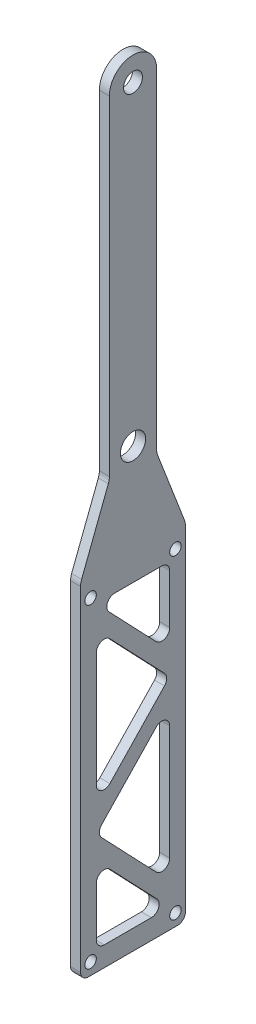
SolidWorks part; units mm, degrees
material "6061 Alloy"
ref_plane "Front Plane" through (0, 0, 0) normal (0, 0, 1) x (1, 0, 0)
ref_plane "Top Plane" through (0, 0, 0) normal (0, 1, 0) x (1, 0, 0)
ref_plane "Right Plane" through (0, 0, 0) normal (1, 0, 0) x (0, 0, -1)
sketch "Sketch1" plane through (0, 0, 0) normal (1, 0, 0) x (0, 0, -1)
  line L0 (-13.4747, 0) -> (13.4747, 0) construction
  line L1 (0, 0) -> (0, 35) construction
  line L2 (-13.4747, 0) -> (0, 35) construction
  line L3 (0, 35) -> (13.4747, 0) construction
  line L4 (13.4747, 0) -> (-13.4747, 0) construction
  line L5 (20.7574, -5) -> (-20.7574, -5)
  line L6 (-20.7574, -5) -> (0, 48.9165)
  line L7 (0, 48.9165) -> (20.7574, -5)
  line L8 (0, 35) -> (0, 135) construction
  line L9 (0, 35) -> (0, 135) construction
  line L12 (-7.5, 35) -> (-7.5, 135)
  line L13 (7.5, 35) -> (7.5, 135)
  line L14 (-7.5, 35) -> (-7.5, 29.4356)
  line L15 (7.5, 35) -> (7.5, 29.4356)
  line L16 (-13.4747, 0) -> (13.4747, 0) construction
  line L17 (-13.4747, 0) -> (-13.4747, -100) construction
  line L18 (13.4747, 0) -> (13.4747, -100) construction
  line L19 (-13.4747, -100) -> (13.4747, -100) construction
  line L20 (-20.7574, -5) -> (20.7574, -5)
  line L21 (-20.7574, -5) -> (-20.7574, -103.81)
  line L22 (20.7574, -5) -> (20.7574, -103.81)
  line L23 (-20.7574, -103.81) -> (20.7574, -103.81)
  circle A0 centre (-13.4747, 0) radius 1.8288
  circle A1 centre (0, 35) radius 4
  circle A2 centre (13.4747, 0) radius 1.8288
  circle A3 centre (0, 135) radius 3
  arc A6 (-7.5, 35) -> (7.5, 35) centre (0, 35) ccw
  arc A7 (7.5, 135) -> (-7.5, 135) centre (0, 135) ccw
  circle A8 centre (-13.4747, -100) radius 1.8288
  circle A9 centre (13.4747, -100) radius 1.8288
  point P4 (0, 0)
  point P14 (0, 85)
  dimension "D3" = 3.6576
  dimension "D4" = 8
  dimension "D7" = 6
  dimension "D1" = 26.9494
  dimension "D5" = 100
  dimension "D6" = 15
  dimension "D8" = 100
  dimension "D9" = 3.81
  dimension "D10" = 35
  dimension "D2" = 5
extrude "Boss-Extrude1" add sketch "Sketch1" along normal blind 3.175 contours A6 L6 L5 L7 A2 A0 | L6 A6 L7 A1 | L13 A7 L12 A6 L6 A1 L7 A3 | A1 L7 L6 | A6 L7 L15 | A6 L14 L6 | A8 | A9 | L20 L21 L23 L22
sketch "Sketch2" plane through (3.175, 0, 0) normal (1, 0, 0) x (0, 0, -1)
  line L0 (-11.645, -2.5) -> (11.645, -2.5) construction
  line L1 (-11.645, -97.5) -> (11.645, -97.5) construction
  line L2 (11.645, -97.5) -> (11.645, -2.5) construction
  line L3 (-11.645, -97.5) -> (-11.645, -2.5) construction
  line L6 (11.645, -37.7891) -> (-11.645, -62.2109) construction
  line L7 (11.645, -2.5) -> (-11.645, -2.5)
  line L8 (-11.645, -2.5) -> (11.645, -26.9218)
  line L9 (11.645, -26.9218) -> (11.645, -2.5)
  line L10 (-11.645, -9.7449) -> (11.645, -34.1667)
  line L11 (11.645, -34.1667) -> (-11.645, -58.5884)
  line L12 (-11.645, -58.5884) -> (-11.645, -34.1667)
  line L13 (-11.645, -34.1667) -> (-11.645, -9.7449)
  line L14 (-11.645, -73.0782) -> (-11.645, -97.5)
  line L15 (-11.645, -97.5) -> (11.645, -97.5)
  line L16 (11.645, -97.5) -> (-11.645, -73.0782)
  line L17 (11.645, -41.4116) -> (11.645, -65.8333)
  line L18 (11.645, -65.8333) -> (11.645, -90.2551)
  line L19 (11.645, -90.2551) -> (-11.645, -65.8333)
  line L20 (-11.645, -65.8333) -> (11.645, -41.4116)
  line L21 (16.645, -1056.0877) -> (16.645, 48943.9123) construction
  line L22 (-16.645, -1060.2922) -> (-16.645, 48939.7078) construction
  line L23 (16.645, 29.4356) -> (-16.645, 29.4356) construction
  line L24 (-20.7574, -103.81) -> (-16.645, -103.81)
  line L25 (-20.7574, -103.81) -> (-20.7574, 29.4356)
  line L26 (-16.645, -103.81) -> (-16.645, 29.4356)
  line L27 (-20.7574, 29.4356) -> (-16.645, 29.4356)
  line L28 (-20.7574, -103.81) -> (20.7574, -103.81) construction
  line L29 (20.7574, -103.81) -> (16.645, -103.81)
  line L30 (20.7574, -103.81) -> (20.7574, 29.4356)
  line L31 (16.645, -103.81) -> (16.645, 29.4356)
  line L32 (20.7574, 29.4356) -> (16.645, 29.4356)
  circle A0 centre (13.4747, 0) radius 1.8288 construction
  circle A1 centre (13.4747, -100) radius 1.8288 construction
  point P6 (11.645, -50)
  point P10 (0, 29.4356)
  point P21 (0, -50)
  dimension "D1" = 33.29
  dimension "D2" = 5
  dimension "D3" = 2.5
  dimension "D4" = 2.5
  dimension "D5" = 5
  dimension "D6" = 2.5
  dimension "D8" = 5
  dimension "D7" = 2
extrude "Cut-Extrude1" cut sketch "Sketch2" against normal up to next
fillet "Fillet3" radius 2.5 14 edges at (1.5875, -58.5884, 11.645) (1.5875, -34.1667, -11.645) (1.5875, -97.5, -11.645) (1.5875, -73.0782, 11.645) (1.5875, -97.5, 11.645) (1.5875, -26.9218, -11.645) (1.5875, -2.5, -11.645) (1.5875, -9.7449, 11.645) (1.5875, -2.5, 11.645) (1.5875, -90.2551, -11.645) (1.5875, -41.4116, -11.645) (1.5875, -65.8333, 11.645) (1.5875, -103.81, 16.645) (1.5875, -103.81, -16.645)
fillet "Fillet4" radius 5 4 edges at (1.5875, 29.4356, -7.5) (1.5875, 29.4356, 7.5) (1.5875, 5.6818, 16.645) (1.5875, 5.6818, -16.645)
